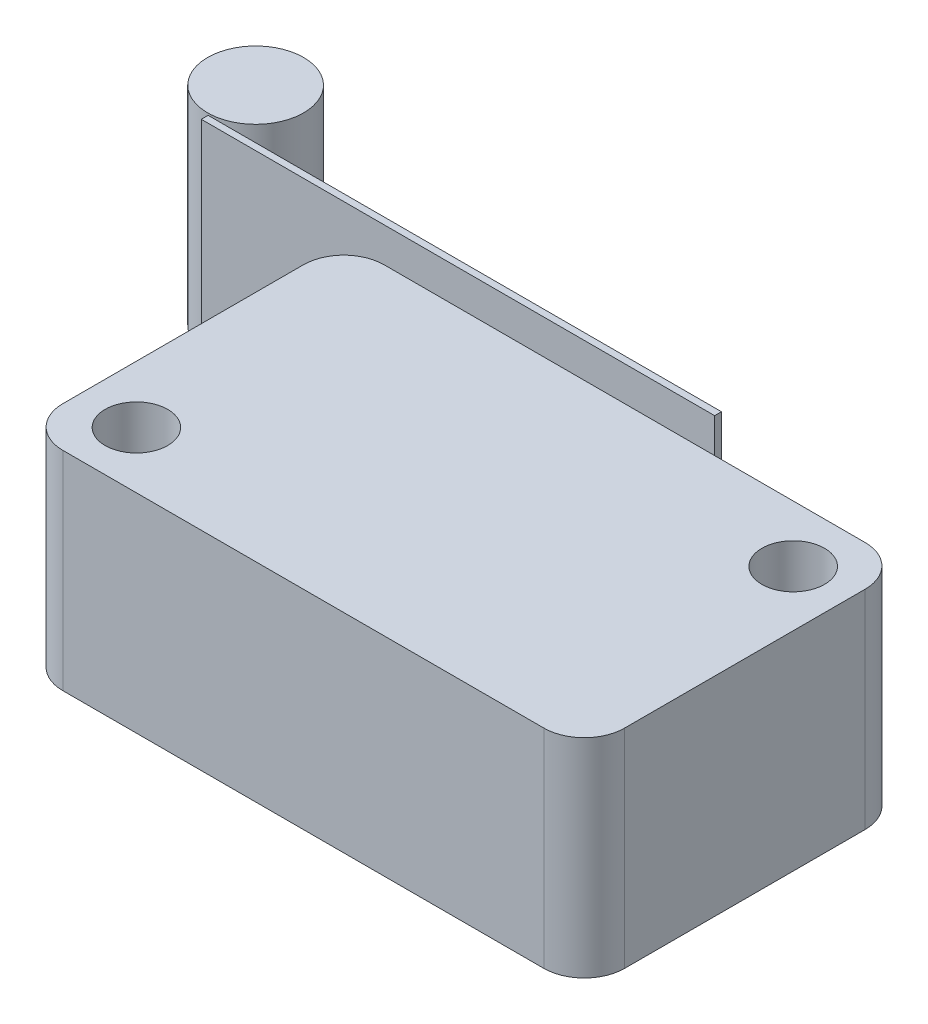
SolidWorks part; units mm, degrees
ref_plane "Front Plane" through (0, 0, 0) normal (0, 0, 1) x (1, 0, 0)
ref_plane "Top Plane" through (0, 0, 0) normal (0, 1, 0) x (1, 0, 0)
ref_plane "Right Plane" through (0, 0, 0) normal (1, 0, 0) x (0, 0, -1)
sketch "Sketch1" plane through (0, 0, 0) normal (0, 1, 0) x (1, 0, 0)
  line L0 (-14.3775, 0.2731) -> (13.4225, 0.2731) construction
  line L1 (13.4225, -7.6769) -> (-14.3775, -7.6769)
  line L2 (13.4225, -7.6769) -> (13.4225, 8.2231)
  line L3 (13.4225, 8.2231) -> (-14.3775, 8.2231)
  line L4 (-14.3775, -7.6769) -> (-14.3775, 8.2231)
  line L5 (13.4225, -7.6769) -> (-14.3775, 8.2231) construction
  line L6 (-0.4775, 8.2231) -> (-0.4775, -7.6769) construction
  circle A0 centre (10.6621, 5.4231) radius 1.55
  circle A1 centre (-11.5379, -4.8769) radius 1.55
  point P0 (0, 0)
  dimension "D6" = 3.1
  dimension "D1" = 27.8
  dimension "D2" = 15.9
  dimension "D3" = 5.15
  dimension "D4" = 5.15
  dimension "D5" = 22.2
extrude "Boss-Extrude1" add sketch "Sketch1" along normal blind 10.3
fillet "Fillet1" radius 2 4 edges at (13.4225, 5.15, 7.6769) (-14.3775, 5.15, 7.6769) (-14.3775, 5.15, -8.2231) (13.4225, 5.15, -8.2231)
sketch "Sketch2" plane through (0, 10.3, 0) normal (0, 1, 0) x (1, 0, 0)
  line L0 (2.2621, 9.9356) -> (-23.1379, 9.9356)
  line L2 (11.4225, 8.2231) -> (-12.3775, 8.2231) construction
  line L3 (-23.1379, 9.9356) -> (-23.1379, 10.2727)
  line L4 (-23.1379, 10.2727) -> (2.2621, 10.2727)
  line L5 (2.2621, 10.2727) -> (2.2621, 9.9356)
  circle A0 centre (10.6621, 5.4231) radius 1.55 construction
  dimension "D1" = 8.4
  dimension "D2" = 25.4
extrude "Boss-Extrude2" add sketch "Sketch2" against normal blind 10.3 separate body
sketch "Sketch3" plane through (-46.2175, 0, 0) normal (0, -1, 0) x (-1, 0, 0)
  circle A0 centre (-22.9602, 12.7417) radius 2.375
  dimension "D1" = 4.75
extrude "Boss-Extrude3" add sketch "Sketch3" against normal blind 10.3 separate body
